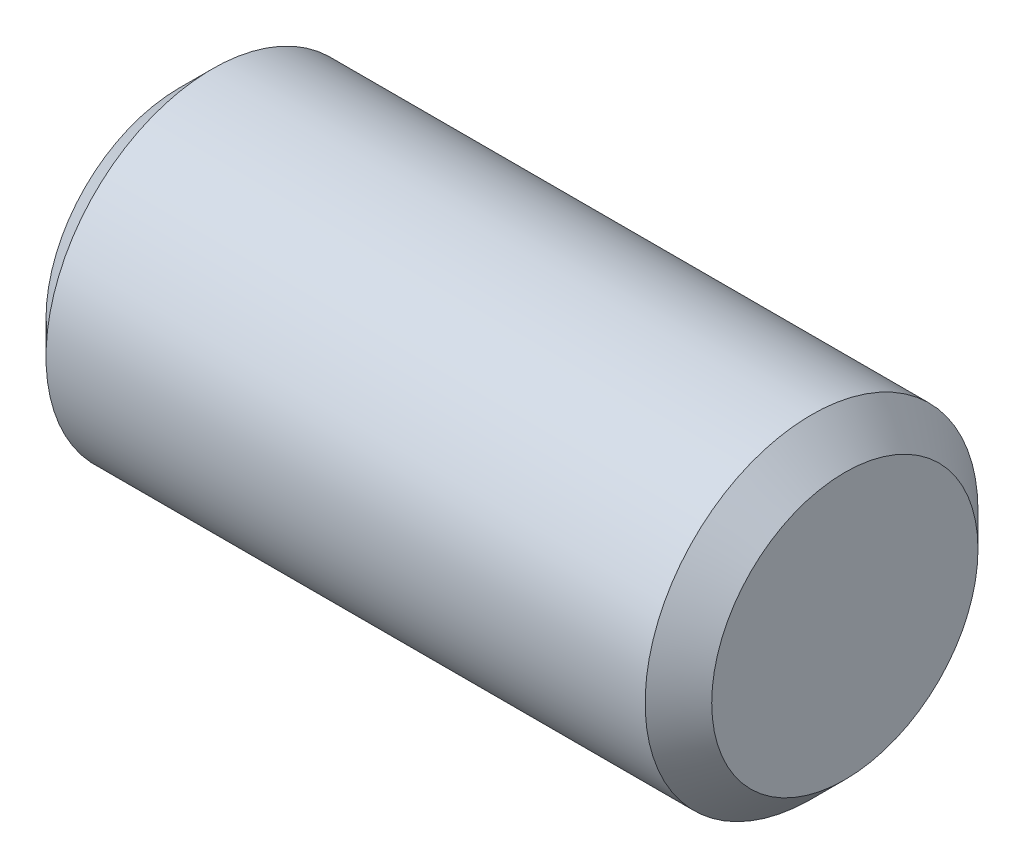
SolidWorks part; units mm, degrees
material "1023 Carbon Steel Sheet (SS)"
ref_plane "Front" through (0, 0, 0) normal (0, 0, 1) x (1, 0, 0)
ref_plane "Top" through (0, 0, 0) normal (0, 1, 0) x (1, 0, 0)
ref_plane "Right" through (0, 0, 0) normal (1, 0, 0) x (0, 0, -1)
sketch "Sketch1" plane through (0, 0, 0) normal (0, 0, 1) x (1, 0, 0)
  line L0 (-3.175, 0) -> (3.175, 0) construction
  line L1 (3.175, 1.5875) -> (3.175, -1.5875) construction
  line L2 (-3.175, 1.5875) -> (-3.175, -1.5875) construction
  dimension "Length" = 6.35
  dimension "Diameter" = 3.175
sketch "Sketch2" plane through (0, 0, 0) normal (1, 0, 0) x (0, 0, -1)
  circle A0 centre (0, 0) radius 1.5875
extrude "Extrude1" add sketch "Sketch2" against normal up to vertex (3.175 mm away) and the other way up to vertex (3.175 mm away) up to point (-3.175, 1.5875, 0) other way up to point (3.175, 1.5875, 0)
chamfer "Chamfer1" distance 0.3175 angle 45 2 edges at (3.175, 0, -1.5875) (-3.175, 0, -1.5875)
equation "\"D1@Chamfer1\" = \"Diameter@Sketch1\"*.1"
